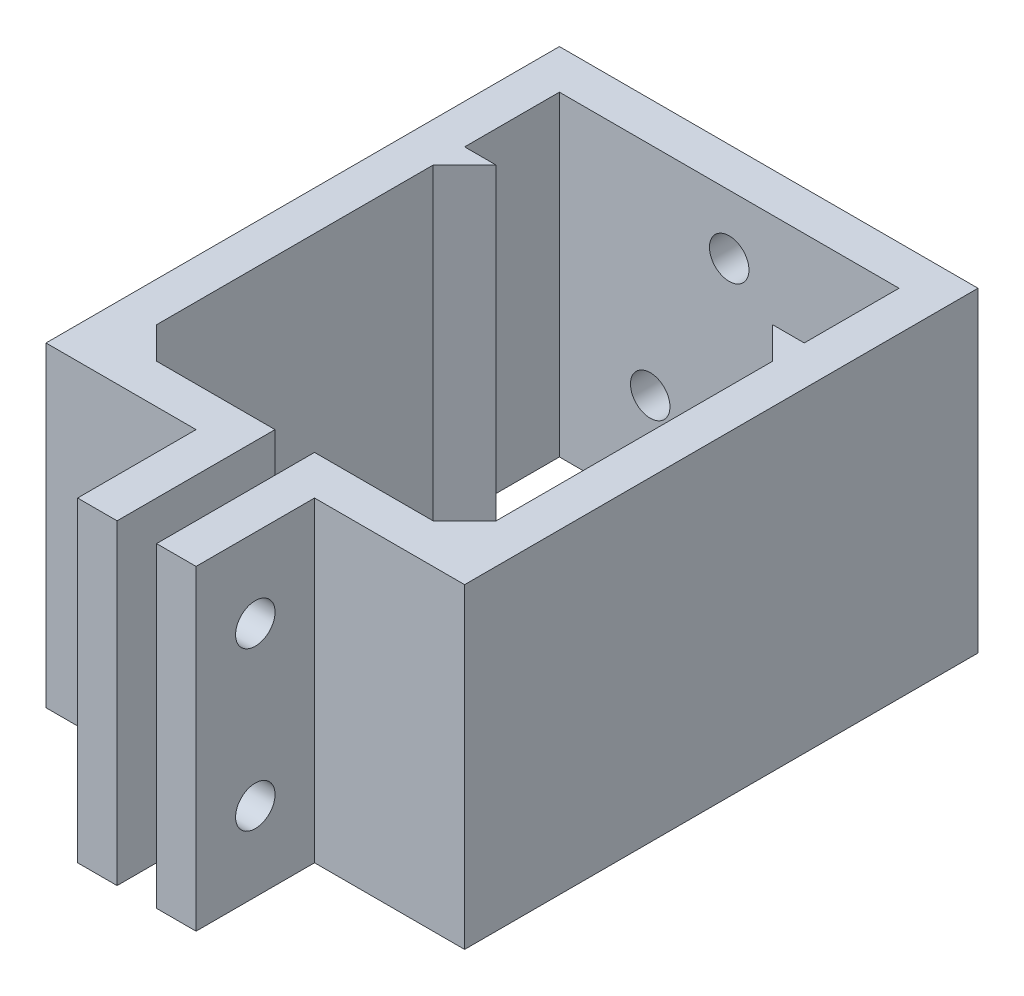
SolidWorks part; units mm, degrees
ref_plane "Спереди" through (0, 0, 0) normal (0, 0, 1) x (1, 0, 0)
ref_plane "Сверху" through (0, 0, 0) normal (0, 1, 0) x (1, 0, 0)
ref_plane "Справа" through (0, 0, 0) normal (1, 0, 0) x (0, 0, -1)
sketch "Эскиз1" plane through (0, 0, 0) normal (0, 1, 0) x (1, 0, 0)
  line L0 (0, 0) -> (0, 65)
  line L1 (0, 65) -> (53, 65)
  line L2 (53, 65) -> (53, 0)
  line L3 (53, 0) -> (34, 0)
  line L4 (34, 0) -> (34, -15)
  line L5 (34, -15) -> (29, -15)
  line L6 (29, -15) -> (29, 5)
  line L7 (29, 5) -> (48, 5)
  line L8 (48, 5) -> (48, 60)
  line L9 (48, 60) -> (5, 60)
  line L10 (5, 60) -> (5, 5)
  line L11 (5, 5) -> (24, 5)
  line L12 (24, 5) -> (24, -15)
  line L13 (24, -15) -> (19, -15)
  line L14 (19, -15) -> (19, 0)
  line L15 (19, 0) -> (0, 0)
  dimension "D1" = 55
  dimension "D2" = 5
  dimension "D3" = 43
  dimension "D4" = 5
  dimension "D5" = 5
  dimension "D6" = 53
  dimension "D7" = 5
  dimension "D8" = 15
extrude "main" add sketch "Эскиз1" along normal blind 40
chamfer "Фаска1" distance 4 angle 45 2 edges at (48, 20, -5) (5, 20, -5)
sketch "Эскиз2" plane through (0, 0, -65) normal (0, 0, -1) x (-1, 0, 0)
  line L0 (-26.5, 40) -> (-26.5, 0) construction
  line L1 (-53, 40) -> (0, 40) construction
  line L2 (-53, 0) -> (0, 0) construction
  line L3 (-53, 20) -> (0, 20) construction
  line L4 (-53, 40) -> (-53, 0) construction
  line L5 (0, 40) -> (0, 0) construction
  circle A0 centre (-26.5, 20) radius 12.5 construction
  circle A1 centre (-26.5, 32.5) radius 2.5
  circle A2 centre (-36.5, 12.5) radius 2.5
  circle A3 centre (-16.5, 12.5) radius 2.5
  point P12 (-26.5, 20)
  point P15 (-26.5, 32.5)
  dimension "D1" = 25
  dimension "D2" = 5
  dimension "D3" = 20
extrude "holes" cut sketch "Эскиз2" against normal up to next
sketch "Эскиз3" plane through (0, 0, 0) normal (0, 1, 0) x (1, 0, 0)
  line L0 (5, 44) -> (5, 48)
  line L1 (5, 9) -> (5, 60) construction
  line L2 (5, 48) -> (9, 48)
  line L3 (9, 48) -> (5, 44)
  line L4 (24, 5) -> (9, 5) construction
  line L5 (26.5, 65) -> (26.5, 5) construction
  line L6 (53, 65) -> (0, 65) construction
  line L7 (44, 5) -> (29, 5) construction
  line L8 (44, 48) -> (48, 44)
  line L9 (48, 48) -> (44, 48)
  line L10 (48, 44) -> (48, 48)
  dimension "D1" = 4
  dimension "D2" = 43
extrude "Вытянуть3" add sketch "Эскиз3" along normal blind 40
sketch "Эскиз4" plane through (34, 0, 0) normal (1, 0, 0) x (0, 0, -1)
  line L0 (-7.5, 40) -> (-7.5, 0) construction
  line L1 (-15, 40) -> (0, 40) construction
  line L2 (-15, 0) -> (0, 0) construction
  circle A0 centre (-7.5, 10) radius 2.5
  circle A1 centre (-7.5, 30) radius 2.5
  dimension "D1" = 5
  dimension "D2" = 10
  dimension "D3" = 10
extrude "Вытянуть4" cut sketch "Эскиз4" against normal up to surface (15 mm away) up to face at (19, 20, 7.5)
